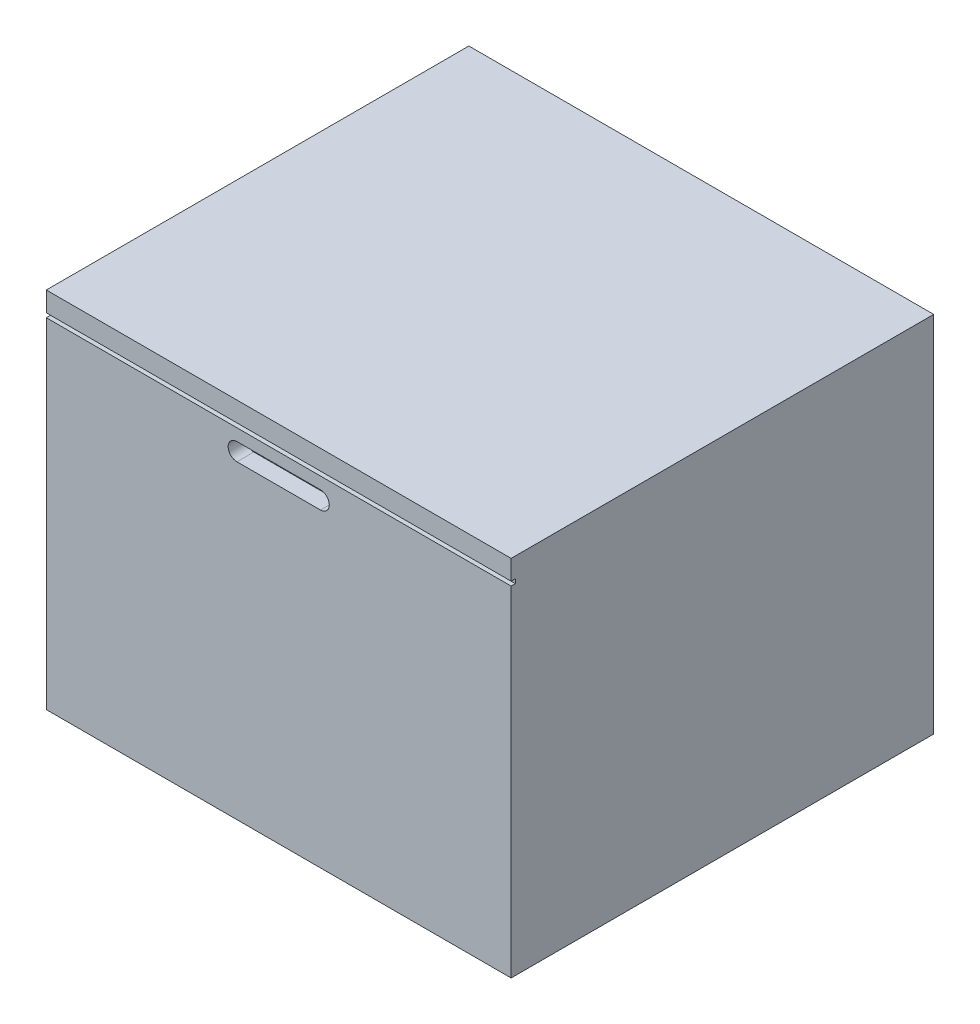
SolidWorks part; units mm, degrees
ref_plane "Front Plane" through (0, 0, 0) normal (0, 0, 1) x (1, 0, 0)
ref_plane "Top Plane" through (0, 0, 0) normal (0, 1, 0) x (1, 0, 0)
ref_plane "Right Plane" through (0, 0, 0) normal (1, 0, 0) x (0, 0, -1)
sketch "Sketch1" plane through (0, 0, 0) normal (0, 1, 0) x (1, 0, 0)
  line L1 (-275, 250) -> (275, 250)
  line L2 (-275, 250) -> (-275, -250)
  line L3 (-275, -250) -> (275, -250)
  line L4 (275, 250) -> (275, -250)
  line L5 (-275, 250) -> (275, -250) construction
  line L6 (-275, -250) -> (275, 250) construction
  point P0 (0, 0)
  dimension "D1" = 500
  dimension "D2" = 550
extrude "Boss-Extrude1" add sketch "Sketch1" along normal blind 430
sketch "Sketch2" plane through (0, 0, 250) normal (0, 0, 1) x (1, 0, 0)
  line L0 (0, 430) -> (0, -49570) construction
  line L1 (-275, 430) -> (275, 430) construction
  line L2 (-49.4488, 377.1061) -> (49.4488, 377.1061) construction
  line L3 (-49.4488, 387.477) -> (49.4488, 387.477)
  line L4 (-49.4488, 366.7351) -> (49.4488, 366.7351)
  arc A0 (-49.4488, 387.477) -> (-49.4488, 366.7351) centre (-49.4488, 377.1061) ccw
  arc A1 (49.4488, 366.7351) -> (49.4488, 387.477) centre (49.4488, 377.1061) ccw
  point P4 (0, 430)
  point P7 (0, 377.1061)
extrude "Cut-Extrude1" cut sketch "Sketch2" against normal blind 20
sketch "Sketch3" plane through (0, 0, 250) normal (0, 0, 1) x (1, 0, 0)
  line L0 (-275, 430) -> (-275, 0) construction
  line L1 (-275, 406.5908) -> (275, 406.5908)
  line L2 (-275, 406.5908) -> (-275, 401.5908)
  line L3 (-275, 401.5908) -> (275, 401.5908)
  line L4 (275, 406.5908) -> (275, 401.5908)
  line L5 (-275, 406.5908) -> (275, 401.5908) construction
  line L6 (-275, 401.5908) -> (275, 406.5908) construction
  line L7 (275, 430) -> (275, 0) construction
  point P4 (0, 404.0908)
  dimension "D1" = 5
extrude "Cut-Extrude2" cut sketch "Sketch3" against normal blind 5
